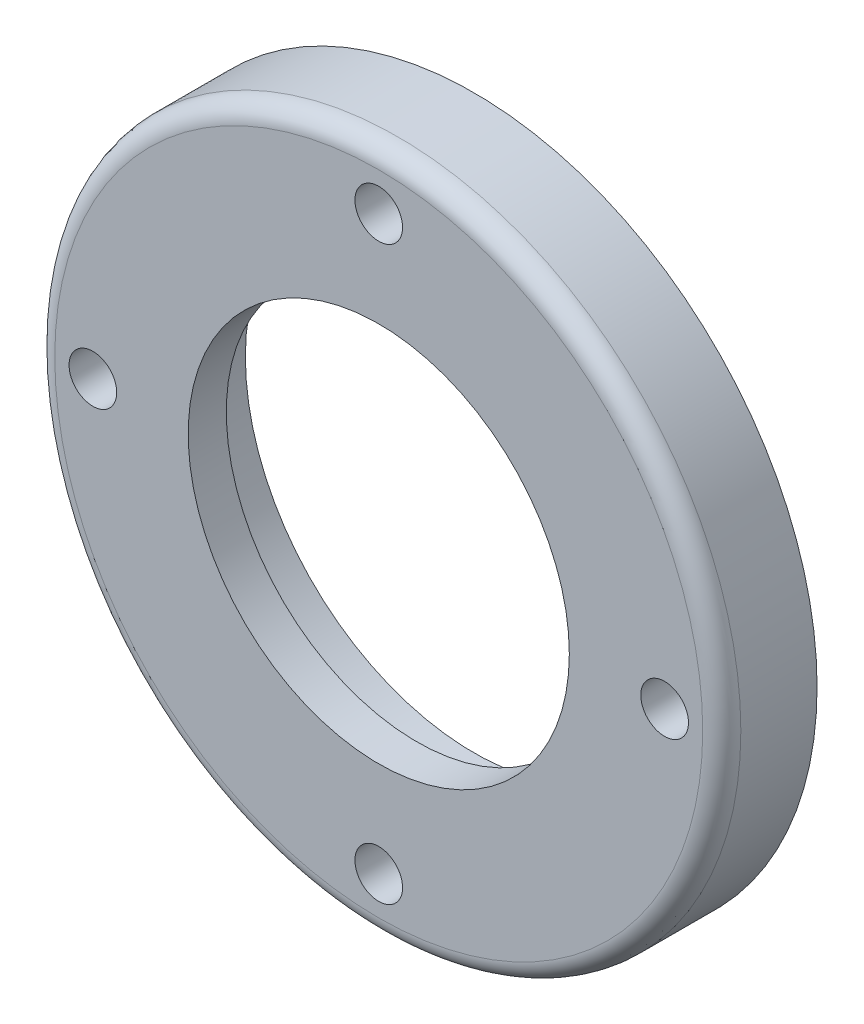
SolidWorks part; units mm, degrees
ref_plane "前视基准面" through (0, 0, 0) normal (0, 0, 1) x (1, 0, 0)
ref_plane "上视基准面" through (0, 0, 0) normal (0, 1, 0) x (1, 0, 0)
ref_plane "右视基准面" through (0, 0, 0) normal (1, 0, 0) x (0, 0, -1)
sketch "草图1" plane through (0, 0, 0) normal (0, 0, 1) x (1, 0, 0)
  line L0 (0, 15) -> (0, -22.7729) construction
  circle A0 centre (0, 0) radius 12
  circle A1 centre (0, 0) radius 18
  circle A2 centre (0, 0) radius 15 construction
  circle A3 centre (0, 15) radius 1.25
  circle A4 centre (-15, 0) radius 1.25
  circle A5 centre (0, -15) radius 1.25
  circle A6 centre (15, 0) radius 1.25
  dimension "D1" = 24
  dimension "D2" = 36
  dimension "D3" = 30
  dimension "D4" = 2.5
  dimension "D5" = 2.5
  dimension "D6" = 2.5
  dimension "D7" = 2.5
extrude "凸台-拉伸1" add sketch "草图1" along normal blind 5
sketch "草图2" plane through (0, 0, 5) normal (0, 0, 1) x (1, 0, 0)
  circle A0 centre (0, 0) radius 12
  circle A1 centre (0, 0) radius 10
  dimension "D1" = 20
extrude "凸台-拉伸2" add sketch "草图2" against normal blind 2
fillet "圆角1" radius 1 1 edges at (18, 0, 5)
